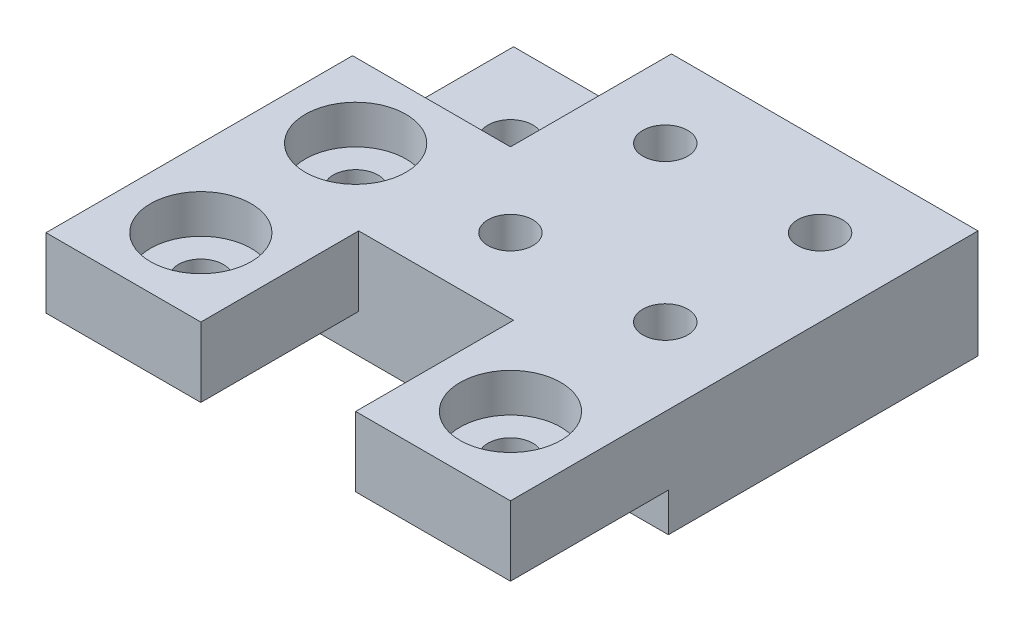
SolidWorks part; units mm, degrees
ref_plane "Alzado" through (0, 0, 0) normal (0, 0, 1) x (1, 0, 0)
ref_plane "Planta" through (0, 0, 0) normal (0, 1, 0) x (1, 0, 0)
ref_plane "Vista lateral" through (0, 0, 0) normal (1, 0, 0) x (0, 0, -1)
sketch "Croquis1" plane through (0, 0, 0) normal (0, 1, 0) x (1, 0, 0)
  line L1 (-50, -50) -> (50, -50)
  line L2 (-50, -50) -> (-50, 50)
  line L3 (-50, 50) -> (50, 50)
  line L4 (50, -50) -> (50, 50)
  line L5 (-50, -50) -> (50, 50) construction
  line L6 (-50, 50) -> (50, -50) construction
  point P0 (0, 0)
  dimension "D1" = 100
  dimension "D2" = 100
extrude "Saliente-Extruir1" add sketch "Croquis1" along normal blind 7
sketch "Croquis2" plane through (0, 7, 0) normal (0, 1, 0) x (1, 0, 0)
  line L45 (-50, 50) -> (-50, -50) construction
  line L50 (-50.2, 50.2) -> (-39.8, 50.2)
  line L55 (-50.2, 50.2) -> (-50.2, 39.8)
  line L60 (-50.2, 39.8) -> (-39.8, 39.8)
  line L65 (-39.8, 50.2) -> (-39.8, 39.8)
  line L70 (50, 50) -> (-50, 50) construction
  line L75 (-30.2, 50.2) -> (-19.8, 50.2)
  line L80 (-30.2, 50.2) -> (-30.2, 39.8)
  line L85 (-30.2, 39.8) -> (-19.8, 39.8)
  line L95 (-19.8, 50.2) -> (-19.8, 39.8)
  line L96 (-10.2, 50.2) -> (0.2, 50.2)
  line L97 (-10.2, 50.2) -> (-10.2, 39.8)
  line L98 (-10.2, 39.8) -> (0.2, 39.8)
  line L99 (0.2, 50.2) -> (0.2, 39.8)
  line L100 (9.8, 50.2) -> (20.2, 50.2)
  line L101 (9.8, 50.2) -> (9.8, 39.8)
  line L102 (9.8, 39.8) -> (20.2, 39.8)
  line L103 (20.2, 50.2) -> (20.2, 39.8)
  line L104 (29.8, 50.2) -> (40.2, 50.2)
  line L105 (29.8, 50.2) -> (29.8, 39.8)
  line L106 (29.8, 39.8) -> (40.2, 39.8)
  line L107 (40.2, 50.2) -> (40.2, 39.8)
  line L108 (-50.2, 30.2) -> (-39.8, 30.2)
  line L109 (-50.2, 30.2) -> (-50.2, 19.8)
  line L110 (-50.2, 19.8) -> (-39.8, 19.8)
  line L111 (-39.8, 30.2) -> (-39.8, 19.8)
  line L112 (-50.2, 10.2) -> (-39.8, 10.2)
  line L113 (-50.2, 10.2) -> (-50.2, -0.2)
  line L114 (-50.2, -0.2) -> (-39.8, -0.2)
  line L115 (-39.8, 10.2) -> (-39.8, -0.2)
  line L116 (-50.2, -9.8) -> (-39.8, -9.8)
  line L117 (-50.2, -9.8) -> (-50.2, -20.2)
  line L118 (-50.2, -20.2) -> (-39.8, -20.2)
  line L119 (-39.8, -9.8) -> (-39.8, -20.2)
  line L120 (-50.2, -29.8) -> (-39.8, -29.8)
  line L121 (-50.2, -29.8) -> (-50.2, -40.2)
  line L122 (-50.2, -40.2) -> (-39.8, -40.2)
  line L123 (-39.8, -29.8) -> (-39.8, -40.2)
  dimension "D3" = 0.2
  dimension "D1" = 10.4
  dimension "D2" = 10.4
  dimension "D4" = 0.2
  dimension "D5" = 5
extrude "Cortar-Extruir1" cut sketch "Croquis2" against normal blind 4.7
sketch "Croquis3" plane through (0, 7, 0) normal (0, 1, 0) x (1, 0, 0)
  line L0 (50, 30) -> (60, 30)
  line L5 (50, 50) -> (60, 50)
  line L6 (50, 50) -> (50, 40)
  line L7 (50, 40) -> (60, 40)
  line L8 (60, 50) -> (60, 40)
  line L9 (50, 30) -> (50, 20)
  line L10 (50, 20) -> (60, 20)
  line L11 (60, 30) -> (60, 20)
  line L12 (50, 10) -> (60, 10)
  line L13 (50, 10) -> (50, 0)
  line L14 (50, 0) -> (60, 0)
  line L15 (60, 10) -> (60, 0)
  line L16 (50, -10) -> (60, -10)
  line L17 (50, -10) -> (50, -20)
  line L18 (50, -20) -> (60, -20)
  line L19 (60, -10) -> (60, -20)
  line L20 (50, -30) -> (60, -30)
  line L21 (50, -30) -> (50, -40)
  line L22 (50, -40) -> (60, -40)
  line L23 (60, -30) -> (60, -40)
  line L24 (-30, -50) -> (-20, -50)
  line L25 (-50, -50) -> (-40, -50)
  line L26 (-50, -50) -> (-50, -60)
  line L27 (-50, -60) -> (-40, -60)
  line L28 (-40, -50) -> (-40, -60)
  line L29 (-30, -50) -> (-30, -60)
  line L30 (-30, -60) -> (-20, -60)
  line L31 (-20, -50) -> (-20, -60)
  line L32 (-10, -50) -> (0, -50)
  line L33 (-10, -50) -> (-10, -60)
  line L34 (-10, -60) -> (0, -60)
  line L35 (0, -50) -> (0, -60)
  line L36 (10, -50) -> (20, -50)
  line L37 (10, -50) -> (10, -60)
  line L38 (10, -60) -> (20, -60)
  line L39 (20, -50) -> (20, -60)
  line L40 (30, -50) -> (40, -50)
  line L41 (30, -50) -> (30, -60)
  line L42 (30, -60) -> (40, -60)
  line L43 (40, -50) -> (40, -60)
  dimension "D1" = 10
  dimension "D2" = 10
  dimension "D4" = 10
  dimension "D5" = 10
  dimension "D3" = 5
extrude "Saliente-Extruir2" add sketch "Croquis3" against normal blind 4.5
sketch "Croquis4" plane through (0, 7, 0) normal (0, 1, 0) x (1, 0, 0)
  line L0 (60, 45) -> (-63.1643, 45) construction
  line L1 (60, 40) -> (60, 50) construction
  line L2 (-45, -60) -> (-45, 61.9533) construction
  line L3 (-50, -60) -> (-40, -60) construction
  circle A0 centre (-45, 45) radius 1.45
  circle A1 centre (-35, 45) radius 1.45
  circle A2 centre (-25, 45) radius 1.45
  circle A3 centre (-15, 45) radius 1.45
  circle A4 centre (-5, 45) radius 1.45
  circle A5 centre (5, 45) radius 1.45
  circle A6 centre (15, 45) radius 1.45
  circle A7 centre (25, 45) radius 1.45
  circle A8 centre (35, 45) radius 1.45
  circle A9 centre (45, 45) radius 1.45
  circle A10 centre (55, 45) radius 1.45
  circle A11 centre (-35, 35) radius 1.45
  circle A12 centre (-25, 35) radius 1.45
  circle A13 centre (-15, 35) radius 1.45
  circle A14 centre (-5, 35) radius 1.45
  circle A15 centre (5, 35) radius 1.45
  circle A16 centre (15, 35) radius 1.45
  circle A17 centre (25, 35) radius 1.45
  circle A18 centre (35, 35) radius 1.45
  circle A19 centre (45, 35) radius 1.45
  circle A20 centre (55, 35) radius 1.45
  circle A21 centre (-35, 25) radius 1.45
  circle A22 centre (-25, 25) radius 1.45
  circle A23 centre (-15, 25) radius 1.45
  circle A24 centre (-5, 25) radius 1.45
  circle A25 centre (5, 25) radius 1.45
  circle A26 centre (15, 25) radius 1.45
  circle A27 centre (25, 25) radius 1.45
  circle A28 centre (35, 25) radius 1.45
  circle A29 centre (45, 25) radius 1.45
  circle A30 centre (55, 25) radius 1.45
  circle A31 centre (-35, 15) radius 1.45
  circle A32 centre (-25, 15) radius 1.45
  circle A33 centre (-15, 15) radius 1.45
  circle A34 centre (-5, 15) radius 1.45
  circle A35 centre (5, 15) radius 1.45
  circle A36 centre (15, 15) radius 1.45
  circle A37 centre (25, 15) radius 1.45
  circle A38 centre (35, 15) radius 1.45
  circle A39 centre (45, 15) radius 1.45
  circle A40 centre (55, 15) radius 1.45
  circle A41 centre (-35, 5) radius 1.45
  circle A42 centre (-25, 5) radius 1.45
  circle A43 centre (-15, 5) radius 1.45
  circle A44 centre (-5, 5) radius 1.45
  circle A45 centre (5, 5) radius 1.45
  circle A46 centre (15, 5) radius 1.45
  circle A47 centre (25, 5) radius 1.45
  circle A48 centre (35, 5) radius 1.45
  circle A49 centre (45, 5) radius 1.45
  circle A50 centre (55, 5) radius 1.45
  circle A51 centre (-35, -5) radius 1.45
  circle A52 centre (-25, -5) radius 1.45
  circle A53 centre (-15, -5) radius 1.45
  circle A54 centre (-5, -5) radius 1.45
  circle A55 centre (5, -5) radius 1.45
  circle A56 centre (15, -5) radius 1.45
  circle A57 centre (25, -5) radius 1.45
  circle A58 centre (35, -5) radius 1.45
  circle A59 centre (45, -5) radius 1.45
  circle A60 centre (55, -5) radius 1.45
  circle A61 centre (-35, -15) radius 1.45
  circle A62 centre (-25, -15) radius 1.45
  circle A63 centre (-15, -15) radius 1.45
  circle A64 centre (-5, -15) radius 1.45
  circle A65 centre (5, -15) radius 1.45
  circle A66 centre (15, -15) radius 1.45
  circle A67 centre (25, -15) radius 1.45
  circle A68 centre (35, -15) radius 1.45
  circle A69 centre (45, -15) radius 1.45
  circle A70 centre (55, -15) radius 1.45
  circle A71 centre (-35, -25) radius 1.45
  circle A72 centre (-25, -25) radius 1.45
  circle A73 centre (-15, -25) radius 1.45
  circle A74 centre (-5, -25) radius 1.45
  circle A75 centre (5, -25) radius 1.45
  circle A76 centre (15, -25) radius 1.45
  circle A77 centre (25, -25) radius 1.45
  circle A78 centre (35, -25) radius 1.45
  circle A79 centre (45, -25) radius 1.45
  circle A80 centre (55, -25) radius 1.45
  circle A81 centre (-35, -35) radius 1.45
  circle A82 centre (-25, -35) radius 1.45
  circle A83 centre (-15, -35) radius 1.45
  circle A84 centre (-5, -35) radius 1.45
  circle A85 centre (5, -35) radius 1.45
  circle A86 centre (15, -35) radius 1.45
  circle A87 centre (25, -35) radius 1.45
  circle A88 centre (35, -35) radius 1.45
  circle A89 centre (45, -35) radius 1.45
  circle A90 centre (55, -35) radius 1.45
  circle A91 centre (-35, -45) radius 1.45
  circle A92 centre (-25, -45) radius 1.45
  circle A93 centre (-15, -45) radius 1.45
  circle A94 centre (-5, -45) radius 1.45
  circle A95 centre (5, -45) radius 1.45
  circle A96 centre (15, -45) radius 1.45
  circle A97 centre (25, -45) radius 1.45
  circle A98 centre (35, -45) radius 1.45
  circle A99 centre (45, -45) radius 1.45
  circle A100 centre (55, -45) radius 1.45
  circle A101 centre (-35, -55) radius 1.45
  circle A102 centre (-25, -55) radius 1.45
  circle A103 centre (-15, -55) radius 1.45
  circle A104 centre (-5, -55) radius 1.45
  circle A105 centre (5, -55) radius 1.45
  circle A106 centre (15, -55) radius 1.45
  circle A107 centre (25, -55) radius 1.45
  circle A108 centre (35, -55) radius 1.45
  circle A109 centre (45, -55) radius 1.45
  circle A110 centre (55, -55) radius 1.45
  circle A111 centre (-45, 35) radius 1.45
  circle A112 centre (-45, 25) radius 1.45
  circle A113 centre (-45, 15) radius 1.45
  circle A114 centre (-45, 5) radius 1.45
  circle A115 centre (-45, -5) radius 1.45
  circle A116 centre (-45, -15) radius 1.45
  circle A117 centre (-45, -25) radius 1.45
  circle A118 centre (-45, -35) radius 1.45
  circle A119 centre (-45, -45) radius 1.45
  circle A120 centre (-45, -55) radius 1.45
  dimension "D1" = 2.9
  dimension "D2" = 11
extrude "Cortar-Extruir2" cut sketch "Croquis4" against normal blind 7
sketch "Croquis5" plane through (0, 7, 0) normal (0, 1, 0) x (1, 0, 0)
  circle A0 centre (-45, 45) radius 3.25
  circle A1 centre (-35, 45) radius 3.25
  circle A2 centre (-25, 45) radius 3.25
  circle A3 centre (-15, 45) radius 3.25
  circle A4 centre (-5, 45) radius 3.25
  circle A5 centre (5, 45) radius 3.25
  circle A6 centre (15, 45) radius 3.25
  circle A7 centre (25, 45) radius 3.25
  circle A8 centre (35, 45) radius 3.25
  circle A9 centre (45, 45) radius 3.25
  circle A10 centre (55, 45) radius 3.25
  circle A20 centre (55, 35) radius 3.25
  circle A30 centre (55, 25) radius 3.25
  circle A40 centre (55, 15) radius 3.25
  circle A50 centre (55, 5) radius 3.25
  circle A60 centre (55, -5) radius 3.25
  circle A70 centre (55, -15) radius 3.25
  circle A80 centre (55, -25) radius 3.25
  circle A90 centre (55, -35) radius 3.25
  circle A100 centre (55, -45) radius 3.25
  circle A101 centre (-35, -55) radius 3.25
  circle A102 centre (-25, -55) radius 3.25
  circle A103 centre (-15, -55) radius 3.25
  circle A104 centre (-5, -55) radius 3.25
  circle A105 centre (5, -55) radius 3.25
  circle A106 centre (15, -55) radius 3.25
  circle A107 centre (25, -55) radius 3.25
  circle A108 centre (35, -55) radius 3.25
  circle A109 centre (45, -55) radius 3.25
  circle A110 centre (55, -55) radius 3.25
  circle A111 centre (-45, 35) radius 3.25
  circle A112 centre (-45, 25) radius 3.25
  circle A113 centre (-45, 15) radius 3.25
  circle A114 centre (-45, 5) radius 3.25
  circle A115 centre (-45, -5) radius 3.25
  circle A116 centre (-45, -15) radius 3.25
  circle A117 centre (-45, -25) radius 3.25
  circle A118 centre (-45, -35) radius 3.25
  circle A119 centre (-45, -45) radius 3.25
  circle A120 centre (-45, -55) radius 3.25
  circle A121 centre (-35, 35) radius 3.25 [skipped]
  circle A122 centre (-25, 35) radius 3.25 [skipped]
  circle A123 centre (-15, 35) radius 3.25 [skipped]
  circle A124 centre (-5, 35) radius 3.25 [skipped]
  circle A125 centre (5, 35) radius 3.25 [skipped]
  circle A126 centre (15, 35) radius 3.25 [skipped]
  circle A127 centre (25, 35) radius 3.25 [skipped]
  circle A128 centre (35, 35) radius 3.25 [skipped]
  circle A129 centre (45, 35) radius 3.25 [skipped]
  circle A130 centre (-35, 25) radius 3.25 [skipped]
  circle A131 centre (-25, 25) radius 3.25 [skipped]
  circle A132 centre (-15, 25) radius 3.25 [skipped]
  circle A133 centre (-5, 25) radius 3.25 [skipped]
  circle A134 centre (5, 25) radius 3.25 [skipped]
  circle A135 centre (15, 25) radius 3.25 [skipped]
  circle A136 centre (25, 25) radius 3.25 [skipped]
  circle A137 centre (35, 25) radius 3.25 [skipped]
  circle A138 centre (45, 25) radius 3.25 [skipped]
  circle A139 centre (-35, 15) radius 3.25 [skipped]
  circle A140 centre (-25, 15) radius 3.25 [skipped]
  circle A141 centre (-15, 15) radius 3.25 [skipped]
  circle A142 centre (-5, 15) radius 3.25 [skipped]
  circle A143 centre (5, 15) radius 3.25 [skipped]
  circle A144 centre (15, 15) radius 3.25 [skipped]
  circle A145 centre (25, 15) radius 3.25 [skipped]
  circle A146 centre (35, 15) radius 3.25 [skipped]
  circle A147 centre (45, 15) radius 3.25 [skipped]
  circle A148 centre (-35, 5) radius 3.25 [skipped]
  circle A149 centre (-25, 5) radius 3.25 [skipped]
  circle A150 centre (-15, 5) radius 3.25 [skipped]
  circle A151 centre (-5, 5) radius 3.25 [skipped]
  circle A152 centre (5, 5) radius 3.25 [skipped]
  circle A153 centre (15, 5) radius 3.25 [skipped]
  circle A154 centre (25, 5) radius 3.25 [skipped]
  circle A155 centre (35, 5) radius 3.25 [skipped]
  circle A156 centre (45, 5) radius 3.25 [skipped]
  circle A157 centre (-35, -5) radius 3.25 [skipped]
  circle A158 centre (-25, -5) radius 3.25 [skipped]
  circle A159 centre (-15, -5) radius 3.25 [skipped]
  circle A160 centre (-5, -5) radius 3.25 [skipped]
  circle A161 centre (5, -5) radius 3.25 [skipped]
  circle A162 centre (15, -5) radius 3.25 [skipped]
  circle A163 centre (25, -5) radius 3.25 [skipped]
  circle A164 centre (35, -5) radius 3.25 [skipped]
  circle A165 centre (45, -5) radius 3.25 [skipped]
  circle A166 centre (-35, -15) radius 3.25 [skipped]
  circle A167 centre (-25, -15) radius 3.25 [skipped]
  circle A168 centre (-15, -15) radius 3.25 [skipped]
  circle A169 centre (-5, -15) radius 3.25 [skipped]
  circle A170 centre (5, -15) radius 3.25 [skipped]
  circle A171 centre (15, -15) radius 3.25 [skipped]
  circle A172 centre (25, -15) radius 3.25 [skipped]
  circle A173 centre (35, -15) radius 3.25 [skipped]
  circle A174 centre (45, -15) radius 3.25 [skipped]
  circle A175 centre (-35, -25) radius 3.25 [skipped]
  circle A176 centre (-25, -25) radius 3.25 [skipped]
  circle A177 centre (-15, -25) radius 3.25 [skipped]
  circle A178 centre (-5, -25) radius 3.25 [skipped]
  circle A179 centre (5, -25) radius 3.25 [skipped]
  circle A180 centre (15, -25) radius 3.25 [skipped]
  circle A181 centre (25, -25) radius 3.25 [skipped]
  circle A182 centre (35, -25) radius 3.25 [skipped]
  circle A183 centre (45, -25) radius 3.25 [skipped]
  circle A184 centre (-35, -35) radius 3.25 [skipped]
  circle A185 centre (-25, -35) radius 3.25 [skipped]
  circle A186 centre (-15, -35) radius 3.25 [skipped]
  circle A187 centre (-5, -35) radius 3.25 [skipped]
  circle A188 centre (5, -35) radius 3.25 [skipped]
  circle A189 centre (15, -35) radius 3.25 [skipped]
  circle A190 centre (25, -35) radius 3.25 [skipped]
  circle A191 centre (35, -35) radius 3.25 [skipped]
  circle A192 centre (45, -35) radius 3.25 [skipped]
  circle A193 centre (-35, -45) radius 3.25 [skipped]
  circle A194 centre (-25, -45) radius 3.25 [skipped]
  circle A195 centre (-15, -45) radius 3.25 [skipped]
  circle A196 centre (-5, -45) radius 3.25 [skipped]
  circle A197 centre (5, -45) radius 3.25 [skipped]
  circle A198 centre (15, -45) radius 3.25 [skipped]
  circle A199 centre (25, -45) radius 3.25 [skipped]
  circle A200 centre (35, -45) radius 3.25 [skipped]
  circle A201 centre (45, -45) radius 3.25 [skipped]
  dimension "D1" = 6.5
  dimension "D3" = 11
  dimension "D2" = 11
extrude "Cortar-Extruir4" cut sketch "Croquis5" against normal blind 2.5
sketch "Croquis6" plane through (0, 7, 0) normal (0, 1, 0) x (1, 0, 0)
  line L0 (50, -50) -> (40, -50)
  line L1 (50, -50) -> (50, -49.8)
  line L2 (40, -50) -> (40, -49.8)
  line L3 (49.8, -49.8) -> (40, -49.8)
  line L4 (30, -50) -> (20, -50)
  line L5 (30, -50) -> (30, -49.8)
  line L6 (20, -50) -> (20, -49.8)
  line L7 (30, -49.8) -> (20, -49.8)
  line L8 (10, -50) -> (0, -50)
  line L9 (10, -50) -> (10, -49.8)
  line L10 (0, -50) -> (0, -49.8)
  line L11 (10, -49.8) -> (0, -49.8)
  line L12 (-10, -50) -> (-20, -50)
  line L13 (-10, -50) -> (-10, -49.8)
  line L14 (-20, -50) -> (-20, -49.8)
  line L15 (-10, -49.8) -> (-20, -49.8)
  line L16 (-30, -50) -> (-40, -50)
  line L17 (-30, -50) -> (-30, -49.8)
  line L18 (-40, -50) -> (-40, -49.8)
  line L19 (-30, -49.8) -> (-40, -49.8)
  line L20 (50, -49.8) -> (50, -40)
  line L22 (50, -40) -> (49.8, -40)
  line L23 (49.8, -49.8) -> (49.8, -40)
  line L24 (50, -29.8) -> (50, -20)
  line L25 (50, -29.8) -> (49.8, -29.8)
  line L26 (50, -20) -> (49.8, -20)
  line L27 (49.8, -29.8) -> (49.8, -20)
  line L28 (50, -9.8) -> (50, 0)
  line L29 (50, -9.8) -> (49.8, -9.8)
  line L30 (50, 0) -> (49.8, 0)
  line L31 (49.8, -9.8) -> (49.8, 0)
  line L32 (50, 10.2) -> (50, 20)
  line L33 (50, 10.2) -> (49.8, 10.2)
  line L34 (50, 20) -> (49.8, 20)
  line L35 (49.8, 10.2) -> (49.8, 20)
  line L36 (50, 30.2) -> (50, 40)
  line L37 (50, 30.2) -> (49.8, 30.2)
  line L38 (50, 40) -> (49.8, 40)
  line L39 (49.8, 30.2) -> (49.8, 40)
  dimension "D1" = 0.2
  dimension "D2" = 0.2
  dimension "D3" = 5
extrude "Cortar-Extruir5" cut sketch "Croquis6" against normal blind 7
sketch "Croquis8" plane through (0, 7, 0) normal (0, 1, 0) x (1, 0, 0)
  line L1 (49.8, 40) -> (60, 40)
  line L2 (49.8, 40) -> (49.8, 50)
  line L3 (49.8, 50) -> (60, 50)
  line L4 (60, 40) -> (60, 50)
extrude "Cortar-Extruir7" cut sketch "Croquis8" against normal blind 7
sketch "Croquis9" plane through (0, 0, 0) normal (0, -1, 0) x (1, 0, 0)
  line L0 (-40, 50) -> (-40, 49.8)
  line L1 (-40, 50) -> (-50.0122, 50)
  line L2 (-40, 49.8) -> (-50.0122, 49.8)
  line L3 (-50.0122, 50) -> (-50.0122, 49.8)
  line L4 (-20, 50) -> (-20, 49.8)
  line L5 (-20, 50) -> (-30.0122, 50)
  line L6 (-20, 49.8) -> (-30.0122, 49.8)
  line L7 (-30.0122, 50) -> (-30.0122, 49.8)
  line L8 (0, 50) -> (0, 49.8)
  line L9 (0, 50) -> (-10.0122, 50)
  line L10 (0, 49.8) -> (-10.0122, 49.8)
  line L11 (-10.0122, 50) -> (-10.0122, 49.8)
  line L12 (20, 50) -> (20, 49.8)
  line L13 (20, 50) -> (9.9878, 50)
  line L14 (20, 49.8) -> (9.9878, 49.8)
  line L15 (9.9878, 50) -> (9.9878, 49.8)
  line L16 (40, 50) -> (40, 49.8)
  line L17 (40, 50) -> (29.9878, 50)
  line L18 (40, 49.8) -> (29.9878, 49.8)
  line L19 (29.9878, 50) -> (29.9878, 49.8)
  line L20 (50, -20) -> (50, -30.2)
  line L21 (50, -20) -> (49.8, -20)
  line L22 (50, -30.2) -> (49.8, -30.2)
  line L23 (49.8, -20) -> (49.8, -30.2)
  line L24 (49.8, -50) -> (49.8, -30.2) construction
  line L25 (50, 0) -> (50, -10.2)
  line L26 (50, 0) -> (49.8, 0)
  line L27 (50, -10.2) -> (49.8, -10.2)
  line L28 (49.8, 0) -> (49.8, -10.2)
  line L29 (50, 20) -> (50, 9.8)
  line L30 (50, 20) -> (49.8, 20)
  line L31 (50, 9.8) -> (49.8, 9.8)
  line L32 (49.8, 20) -> (49.8, 9.8)
  line L33 (50, 40) -> (50, 29.8)
  line L34 (50, 40) -> (49.8, 40)
  line L35 (50, 29.8) -> (49.8, 29.8)
  line L36 (49.8, 40) -> (49.8, 29.8)
  dimension "D1" = 0
  dimension "D2" = 4
extrude "Cortar-Extruir9" cut sketch "Croquis9" against normal blind 2.5
sketch "Croquis10" plane through (0, 2.5, 0) normal (0, -1, 0) x (1, 0, 0)
  line L0 (50, 30) -> (50, 29.8)
  line L1 (50, 30) -> (49.8, 30)
  line L2 (50, 29.8) -> (49.8, 29.8)
  line L3 (49.8, 30) -> (49.8, 29.8)
  line L4 (50, 10) -> (50, 9.8)
  line L5 (50, 10) -> (49.8, 10)
  line L6 (49.8, 10) -> (49.8, 9.8)
  line L7 (50, 9.8) -> (49.8, 9.8)
  line L8 (50, -10) -> (50, -10.2)
  line L9 (50, -10) -> (49.8, -10)
  line L10 (49.8, -10) -> (49.8, -10.2)
  line L11 (50, -10.2) -> (49.8, -10.2)
  line L12 (50, -30) -> (50, -30.2)
  line L13 (50, -30) -> (49.8, -30)
  line L14 (49.8, -30) -> (49.8, -30.2)
  line L15 (50, -30.2) -> (49.8, -30.2)
  line L16 (49.8, -20) -> (49.8, -30.2) construction
  dimension "D2" = 0
  dimension "D1" = 4
extrude "Cortar-Extruir11" cut sketch "Croquis10" against normal blind 5
sketch "Croquis11" plane through (0, 7, 0) normal (0, 1, 0) x (1, 0, 0)
  line L1 (-50, -29.8) -> (-20, -29.8)
  line L2 (-50, -29.8) -> (-50, 55.3151)
  line L3 (-50, 55.3151) -> (69.8211, 55.3151)
  line L4 (69.8211, -29.8) -> (69.8211, 55.3151)
  line L5 (-20, -60) -> (69.8211, -60)
  line L6 (-20, -60) -> (-20, -29.8)
  line L8 (69.8211, -60) -> (69.8211, -29.8)
extrude "Cortar-Extruir13" cut sketch "Croquis11" against normal blind 15
